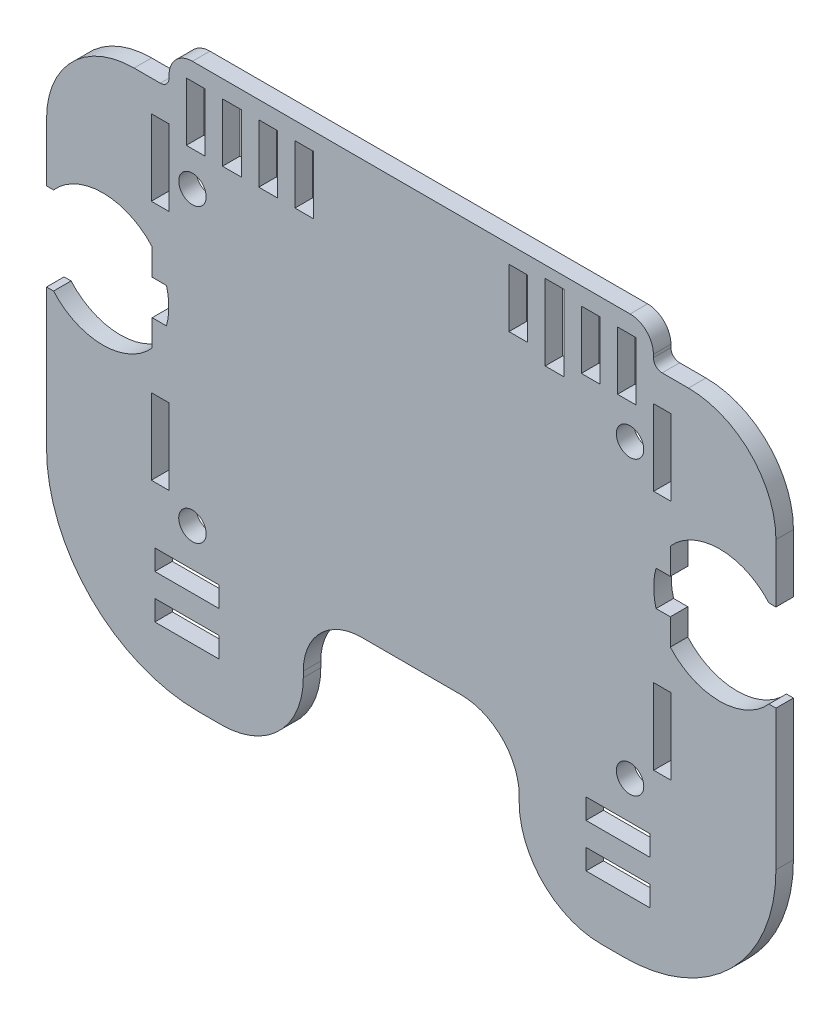
SolidWorks part; units mm, degrees
ref_plane "Přední rovina" through (0, 0, 0) normal (0, 0, 1) x (1, 0, 0)
ref_plane "Horní rovina" through (0, 0, 0) normal (0, 1, 0) x (1, 0, 0)
ref_plane "Pravá rovina" through (0, 0, 0) normal (1, 0, 0) x (0, 0, -1)
sketch "Skica2" plane through (0, 0, 0) normal (0, 0, 1) x (1, 0, 0)
  line L0 (-39.6595, 0) -> (1943.3131, 0) construction
  line L1 (0, -39.6595) -> (0, 1943.3131) construction
  line L2 (-62.5, 7.5) -> (-61.3, 7.5)
  line L3 (-44.3956, 7.5) -> (-44.3956, 3)
  line L4 (-44.3956, -3) -> (-44.3956, -7.5)
  line L5 (-61.3, -7.5) -> (-62.5, -7.5)
  line L6 (-41.5478, 14.2) -> (-41.5478, -3) construction
  line L8 (-62.5, 32.5) -> (-62.5, -16.7803) construction
  line L10 (62.5, 32.5) -> (62.5, -18.975) construction
  line L17 (-43.9478, -44.4435) -> (-32.9478, -44.4435)
  line L18 (-43.9478, -36.9445) -> (-32.9478, -36.9445)
  line L19 (-44.5478, -14.2) -> (-41.5478, -14.2)
  line L20 (-44.5478, 27.2) -> (-41.5478, 27.2)
  line L21 (-44.5478, 27.2) -> (-44.5478, 14.2)
  line L22 (-44.5478, 14.2) -> (-41.5478, 14.2)
  line L23 (-41.5478, 27.2) -> (-41.5478, 14.2)
  line L24 (-44.5478, -27.2) -> (-44.5478, -14.2)
  line L25 (-44.5478, -27.2) -> (-41.5478, -27.2)
  line L26 (-41.5478, -27.2) -> (-41.5478, -14.2)
  line L27 (-62.5, 7.5) -> (-62.5, 17.5)
  line L28 (-62.5, -7.5) -> (-62.5, -16.7803)
  line L29 (44.5478, -27.2) -> (41.5478, -27.2)
  line L30 (44.5478, -27.2) -> (44.5478, -14.2)
  line L31 (41.5478, -27.2) -> (41.5478, -14.2)
  line L32 (44.5478, -14.2) -> (41.5478, -14.2)
  line L33 (44.5478, 14.2) -> (41.5478, 14.2)
  line L34 (44.5478, 27.2) -> (41.5478, 27.2)
  line L35 (41.5478, 27.2) -> (41.5478, 14.2)
  line L36 (44.5478, 27.2) -> (44.5478, 14.2)
  line L41 (44.3956, -3) -> (44.3956, -7.5)
  line L42 (44.3956, 7.5) -> (44.3956, 3)
  line L43 (61.3, -7.5) -> (62.5, -7.5)
  line L44 (62.5, 7.5) -> (61.3, 7.5)
  line L45 (62.5, -7.5) -> (62.5, -18.975)
  line L46 (62.5, 7.5) -> (62.5, 17.5)
  line L47 (-44.3956, 3) -> (-41.9533, 3)
  line L48 (-44.3956, -3) -> (-41.9533, -3)
  line L49 (44.3956, -3) -> (41.9533, -3)
  line L50 (44.3956, 3) -> (41.9533, 3)
  line L51 (-8.5, -32.5) -> (8.5, -32.5)
  line L53 (-62.5, -16.7803) -> (-62.5, -31.5)
  line L57 (62.5, -18.975) -> (62.5, -31.5)
  line L60 (-43.9478, -36.9445) -> (-43.9478, -40.4435)
  line L61 (-43.9478, -40.4435) -> (-32.9478, -40.4435)
  line L62 (-32.9478, -36.9445) -> (-32.9478, -40.4435)
  line L63 (-43.9478, -44.4435) -> (-43.9478, -47.9425)
  line L64 (-43.9478, -47.9425) -> (-32.9478, -47.9425)
  line L65 (-32.9478, -44.4435) -> (-32.9478, -47.9425)
  line L71 (-38.5478, 35.5) -> (-35.3478, 35.5)
  line L72 (-38.5478, 35.5) -> (-38.5478, 25.5)
  line L73 (-38.5478, 25.5) -> (-35.3478, 25.5)
  line L74 (-35.3478, 35.5) -> (-35.3478, 25.5)
  line L78 (35.3478, 35.5) -> (38.5478, 35.5)
  line L79 (35.3478, 35.5) -> (35.3478, 25.5)
  line L80 (35.3478, 25.5) -> (38.5478, 25.5)
  line L81 (38.5478, 35.5) -> (38.5478, 25.5)
  line L82 (29.1478, 35.5) -> (32.3478, 35.5)
  line L83 (29.1478, 35.5) -> (29.1478, 25.5)
  line L84 (29.1478, 25.5) -> (32.3478, 25.5)
  line L85 (32.3478, 35.5) -> (32.3478, 25.5)
  line L90 (-43, 32.5) -> (-47.5, 32.5)
  line L92 (-41.5, 34) -> (-41.5, 34.5)
  line L93 (-37.5, 38.5) -> (37.5, 38.5)
  line L94 (41.5, 34) -> (41.5, 34.5)
  line L95 (43, 32.5) -> (47.5, 32.5)
  line L96 (22.9478, 36.5) -> (26.1478, 36.5)
  line L97 (22.9478, 36.5) -> (22.9478, 23.5)
  line L98 (22.9478, 23.5) -> (26.1478, 23.5)
  line L99 (26.1478, 36.5) -> (26.1478, 23.5)
  line L104 (29.9478, -36.9445) -> (40.9478, -36.9445)
  line L105 (29.9478, -36.9445) -> (29.9478, -40.4435)
  line L106 (29.9478, -40.4435) -> (40.9478, -40.4435)
  line L107 (40.9478, -36.9445) -> (40.9478, -40.4435)
  line L108 (-36.5, -57.5) -> (-32.5, -57.5)
  line L109 (-18.5, -43.5) -> (-18.5, -42.5)
  line L110 (36.5, -57.5) -> (32.5, -57.5)
  line L111 (18.5, -43.5) -> (18.5, -42.5)
  line L120 (-32.3478, 35.5) -> (-29.132, 35.5)
  line L121 (-32.3478, 35.5) -> (-32.3478, 25.5)
  line L122 (-32.3478, 25.5) -> (-29.132, 25.5)
  line L123 (-29.132, 35.5) -> (-29.132, 25.5)
  line L124 (-26.132, 35.5) -> (-22.932, 35.5)
  line L125 (-26.132, 35.5) -> (-26.132, 25.5)
  line L126 (-26.132, 25.5) -> (-22.932, 25.5)
  line L127 (-22.932, 35.5) -> (-22.932, 25.5)
  line L128 (-19.932, 35.5) -> (-16.732, 35.5)
  line L129 (-19.932, 35.5) -> (-19.932, 25.5)
  line L130 (-19.932, 25.5) -> (-16.732, 25.5)
  line L131 (-16.732, 35.5) -> (-16.732, 25.5)
  line L132 (16.7478, 35.5) -> (19.9478, 35.5)
  line L133 (16.7478, 35.5) -> (16.7478, 25.5)
  line L134 (16.7478, 25.5) -> (19.9478, 25.5)
  line L135 (19.9478, 35.5) -> (19.9478, 25.5)
  line L144 (29.9478, -44.4435) -> (40.9478, -44.4435)
  line L145 (29.9478, -44.4435) -> (29.9478, -47.9425)
  line L146 (29.9478, -47.9425) -> (40.9478, -47.9425)
  line L147 (40.9478, -44.4435) -> (40.9478, -47.9425)
  arc A0 (-44.3956, 7.5) -> (-61.3, 7.5) centre (-52.8478, 0) ccw
  arc A2 (-61.3, -7.5) -> (-44.3956, -7.5) centre (-52.8478, 0) ccw
  circle A3 centre (-52.8478, 0) radius 11.3 construction
  arc A5 (44.3956, 7.5) -> (61.3, 7.5) centre (52.8478, 0) cw
  arc A6 (61.3, -7.5) -> (44.3956, -7.5) centre (52.8478, 0) cw
  arc A19 (-41.9533, 3) -> (-41.9533, -3) centre (-52.8478, 0) cw
  arc A20 (41.9533, 3) -> (41.9533, -3) centre (52.8478, 0) ccw
  arc A21 (8.5, -32.5) -> (18.5, -42.5) centre (8.5, -42.5) cw
  arc A22 (-8.5, -32.5) -> (-18.5, -42.5) centre (-8.5, -42.5) ccw
  arc A25 (62.5, -31.5) -> (36.5, -57.5) centre (36.5, -31.5) cw
  arc A26 (-62.5, -31.5) -> (-36.5, -57.5) centre (-36.5, -31.5) ccw
  arc A27 (37.5, 38.5) -> (41.5, 34.5) centre (37.5, 34.5) cw
  arc A28 (-41.5, 34.5) -> (-37.5, 38.5) centre (-37.5, 34.5) cw
  arc A29 (47.5, 32.5) -> (62.5, 17.5) centre (47.5, 17.5) cw
  arc A30 (-47.5, 32.5) -> (-62.5, 17.5) centre (-47.5, 17.5) ccw
  arc A31 (43, 32.5) -> (41.5, 34) centre (43, 34) cw
  arc A32 (-43, 32.5) -> (-41.5, 34) centre (-43, 34) ccw
  arc A33 (-18.5, -43.5) -> (-32.5, -57.5) centre (-32.5, -43.5) cw
  arc A34 (32.5, -57.5) -> (18.5, -43.5) centre (32.5, -43.5) cw
  circle A35 centre (-37.4978, 19.55) radius 2.35
  circle A36 centre (-37.5, -30.45) radius 2.35
  circle A38 centre (37.4978, -30.45) radius 2.35
  circle A39 centre (37.4978, 19.55) radius 2.35
  point P26 (0, 0)
  point P82 (-18.5, -57.5)
  point P94 (-18.5, -57.5)
  point P104 (-62.5, -57.5)
  point P107 (-19.932, 30.5)
  point P112 (30.7478, 35.5)
  point P117 (-41.5, 38.5)
  point P128 (-41.5, 32.5)
  point P138 (-22.932, 30.5)
  point P146 (0, 0)
  point P147 (0, 0)
  dimension "D1" = 22.6
  dimension "D2" = 6
  dimension "D17" = 3.2
  dimension "D19" = 3
  dimension "D23" = 10
  dimension "D24" = 14
  dimension "D34" = 4
  dimension "D35" = 15
  dimension "D36" = 1.5
  dimension "D21" = 14
  dimension "D65" = 30.45
  dimension "D67" = 4.05
  dimension "D73" = 19.55
  dimension "D3" = 15
  dimension "D4" = 1.2
  dimension "D5" = 125
  dimension "D7" = 3.499
  dimension "D8" = 11
  dimension "D9" = 3.2
  dimension "D10" = 13
  dimension "D11" = 3
  dimension "D12" = 14.2
  dimension "D13" = 10
  dimension "D14" = 3
  dimension "D15" = 3
  dimension "D16" = 3
  dimension "D18" = 3
  dimension "D20" = 3
  dimension "D22" = 44
  dimension "D25" = 3
  dimension "D26" = 21
  dimension "D27" = 21
  dimension "D28" = 10
  dimension "D29" = 10
  dimension "D30" = 3.2
  dimension "D31" = 3.2
  dimension "D32" = 3.2
  dimension "D33" = 6
  dimension "D37" = 13
  dimension "D38" = 2
  dimension "D39" = 0
  dimension "D40" = 4
  dimension "D41" = 0.6
  dimension "D42" = 0.6
  dimension "D43" = 36.6798
  dimension "D44" = 3.2
  dimension "D45" = 3
  dimension "D46" = 3.2
  dimension "D47" = 3
  dimension "D48" = 3
  dimension "D49" = 3
  dimension "D50" = 0
  dimension "D51" = 0
  dimension "D52" = 10
  dimension "D53" = 3
  dimension "D54" = 3
  dimension "D55" = 3
  dimension "D56" = 0
  dimension "D57" = 0
  dimension "D58" = 4
  dimension "D59" = 10
  dimension "D60" = 10
  dimension "D61" = 10
  dimension "D62" = 10
  dimension "D63" = 10
  dimension "D64" = 3.7
  dimension "D66" = 19.55
  dimension "D68" = 4.05
  dimension "D69" = 30.45
  dimension "D70" = 4.05
  dimension "D72" = 25
extrude "Přidat vysunutím1" add sketch "Skica2" along normal blind 3
